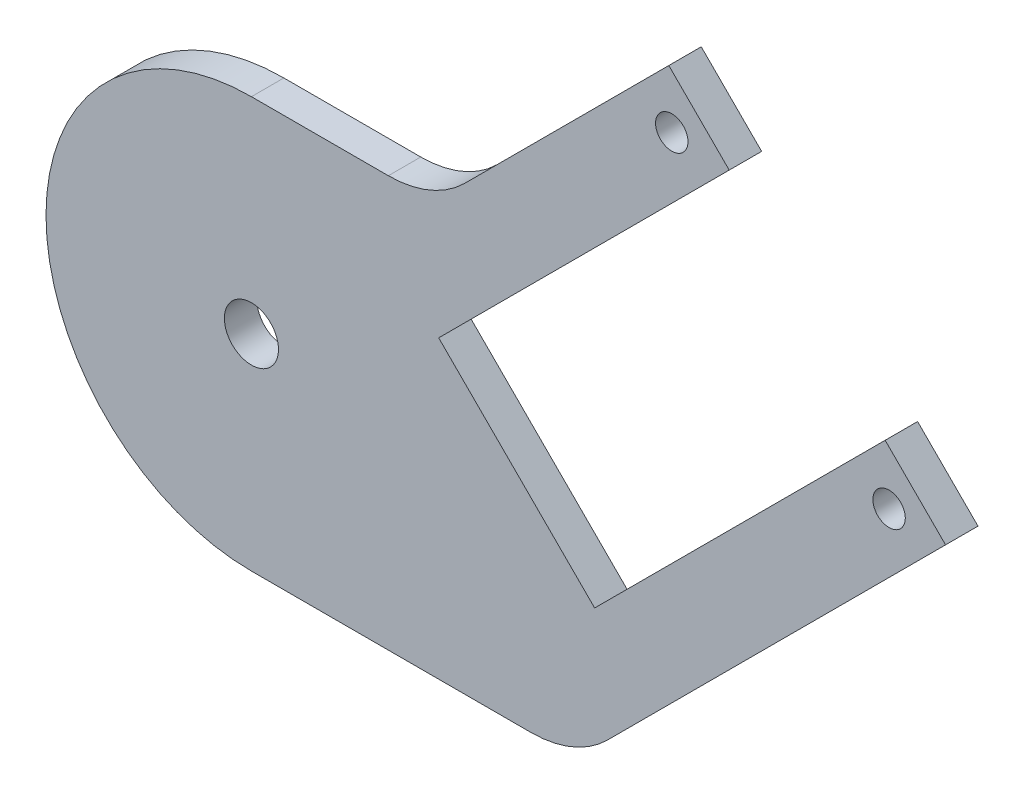
SolidWorks part; units mm, degrees
material "Acrylic (Medium-high impact)"
ref_plane "Front Plane" through (0, 0, 0) normal (0, 0, 1) x (1, 0, 0)
ref_plane "Top Plane" through (0, 0, 0) normal (0, 1, 0) x (1, 0, 0)
ref_plane "Right Plane" through (0, 0, 0) normal (1, 0, 0) x (0, 0, -1)
sketch "Sketch1" plane through (0, 0, 0) normal (0, 0, 1) x (1, 0, 0)
  line L0 (51.4027, 28) -> (24.5327, 1.1299) construction
  line L1 (0, -19) -> (30, -19)
  line L2 (17.3202, 8.3424) -> (31.7452, -6.0825)
  line L3 (31.7452, -6.0825) -> (58.6152, 20.7875)
  line L4 (17.3202, 8.3424) -> (44.1902, 35.2125)
  line L5 (30, -19) -> (64.2014, 15.2014)
  line L6 (44.1902, 35.2125) -> (58.6152, 20.7875) construction
  line L7 (64.2014, 15.2014) -> (58.6152, 20.7875)
  line L8 (0, 0) -> (0, 28) construction
  line L9 (44.1902, 35.2125) -> (38.6041, 40.7986)
  line L10 (38.6041, 40.7986) -> (16.8055, 19)
  line L11 (16.8055, 19) -> (0, 19)
  line L12 (0, 0) -> (-19, 0) construction
  line L13 (51.4027, 28) -> (0, 28) construction
  arc A0 (0, 19) -> (0, -19) centre (0, 0) ccw
  circle A1 centre (0, 0) radius 2.5
  dimension "D5" = 5
  dimension "D4" = 36.2
  dimension "D8" = 30
  dimension "D7" = 28
  dimension "D1" = 38
  dimension "D2" = 20.4
  dimension "D3" = 38
  dimension "D6" = 45
extrude "Boss-Extrude1" add sketch "Sketch1" along normal blind 3
sketch "Sketch2" plane through (0, 0, 3) normal (0, 0, 1) x (1, 0, 0)
  line L0 (44.1902, 35.2125) -> (38.6041, 40.7986) construction
  line L1 (44.1902, 35.2125) -> (58.6152, 20.7875) construction
  line L3 (24.5327, 1.1299) -> (51.4027, 28) construction
  line L4 (31.7452, -6.0825) -> (17.3202, 8.3424) construction
  circle A0 centre (38.8781, 35.5749) radius 1.5
  circle A1 centre (58.9776, 15.4754) radius 1.5
  dimension "D1" = 3
  dimension "D2" = 3.5
  dimension "D3" = 28.425
extrude "Cut-Extrude1" cut sketch "Sketch2" against normal through all
fillet "Fillet1" radius 10 2 edges at (16.8055, 19, 1.5) (30, -19, 1.5)
equation "\"D2@Sketch1\"=20.20mm+\"cut_free@Parameters@Parameters.SLDPRT\""
